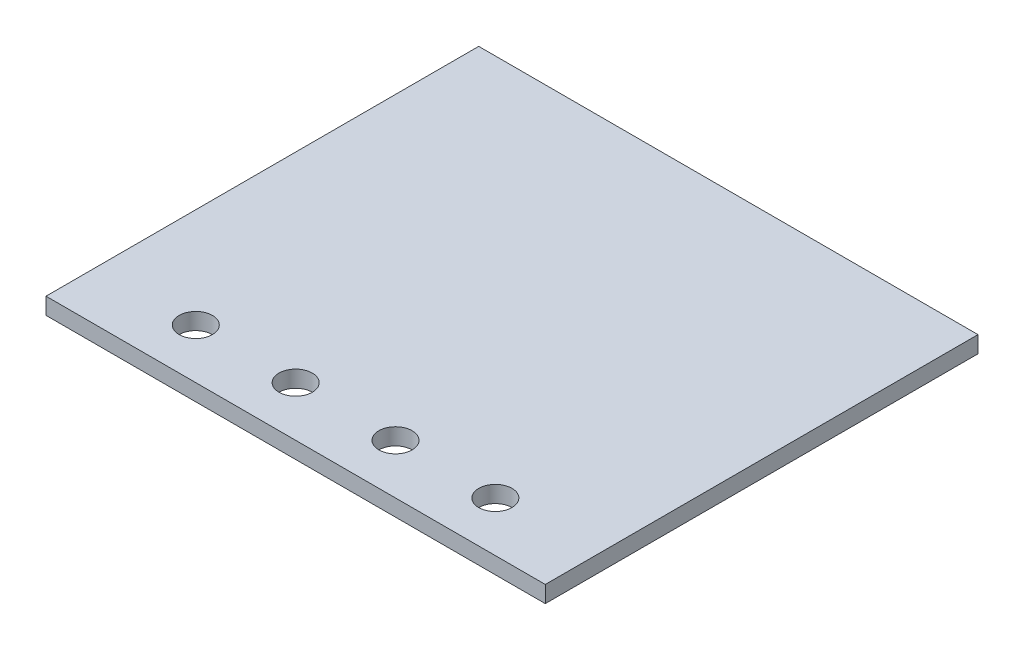
SolidWorks part; units mm, degrees
ref_plane "Front Plane" through (0, 0, 0) normal (0, 0, 1) x (1, 0, 0)
ref_plane "Top Plane" through (0, 0, 0) normal (0, 1, 0) x (1, 0, 0)
ref_plane "Right Plane" through (0, 0, 0) normal (1, 0, 0) x (0, 0, -1)
sketch "Sketch1" plane through (0, 0, 0) normal (0, 1, 0) x (1, 0, 0)
  line L1 (-150, -130) -> (150, -130)
  line L2 (-150, -130) -> (-150, 130)
  line L3 (-150, 130) -> (150, 130)
  line L4 (150, -130) -> (150, 130)
  line L5 (-150, -130) -> (150, 130) construction
  line L6 (-150, 130) -> (150, -130) construction
  point P0 (0, 0)
extrude "Boss-Extrude1" add sketch "Sketch1" along normal blind 10
sketch "Sketch2" plane through (0, 10, 0) normal (0, 1, 0) x (1, 0, 0)
  line L0 (-150, -130) -> (150, -130) construction
  line L1 (-150, 130) -> (-150, -130) construction
  circle A0 centre (-90, -100) radius 10
  dimension "diahole" = 20
  dimension "holewid" = 30
  dimension "holelen" = 60
extrude "Cut-Extrude1" cut sketch "Sketch2" against normal through all contours A0
pattern_linear "LPattern1" count 4 spacing 60 along (1, 0, 0) of "Cut-Extrude1"
pattern_linear "LPattern2" [suppressed] count 3 spacing 60
sketch "Sketch3" plane through (0, 10, 0) normal (0, 1, 0) x (1, 0, 0)
  circle A0 centre (-60, -40) radius 10
  dimension "D3" = 60
  dimension "D1" = 20
  dimension "D2" = 30
extrude "Cut-Extrude2" [suppressed] cut sketch "Sketch3" against normal through all contours A0
pattern_linear "LPattern3" [suppressed] count 4 spacing 60
pattern_linear "LPattern4" [suppressed] count 2 spacing 120
equation "\"d\"= 20mm"
equation "\"diahole@Sketch2\"=\"d\""
equation "\"holewid@Sketch2\"=1.5*\"d\""
equation "\"holelen@Sketch2\"=3*\"d\""
equation "\"D3@LPattern1\"=3*\"d\""
equation "\"len@Sketch1\"=15*\"d\""
equation "\"dep@Sketch1\"=(\"len@Sketch1\"/3)*2+3*\"d\""
equation "\"t\"=10"
equation "\"D1@Boss-Extrude1\"=\"t\""
equation "\"D3@LPattern2\"=3*\"d\""
equation "\"D2@Sketch3\"=1.5*\"d\""
equation "\"D1@Sketch3\"=\"d\""
equation "\"D3@Sketch3\"=3*\"d\""
equation "\"D3@LPattern3\"=3*\"d\""
equation "\"D3@LPattern4\"=6*\"d\""
equation "\"D4@LPattern3\"=3*\"d\""
